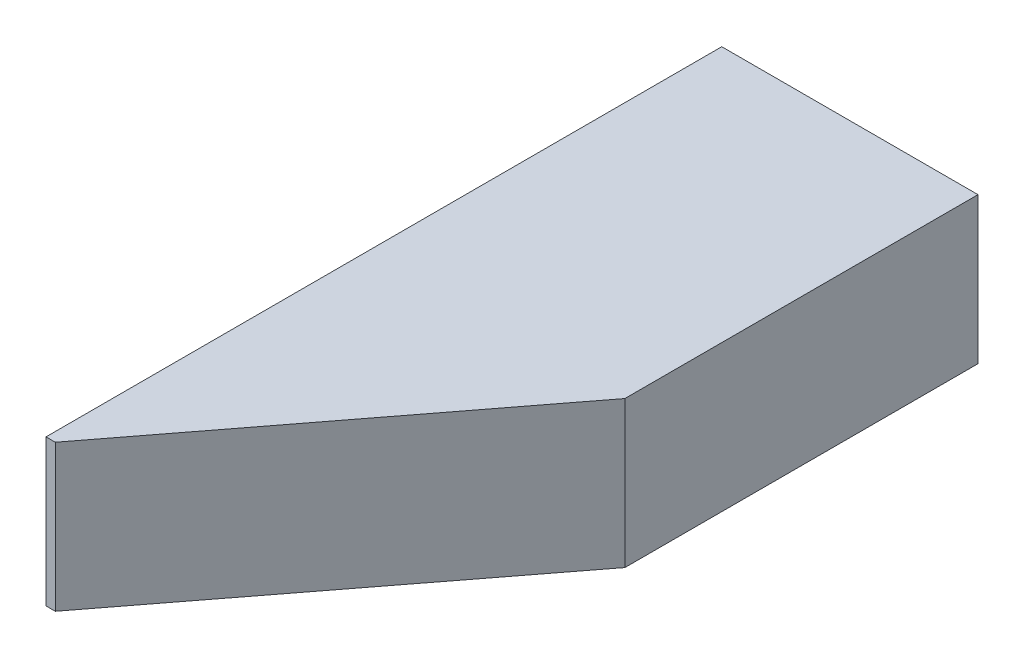
SolidWorks part; units mm, degrees
material "Pine"
ref_plane "X-Y Datum" through (0, 0, 0) normal (0, 0, 1) x (1, 0, 0)
ref_plane "X-Z Datum" through (0, 0, 0) normal (0, 1, 0) x (1, 0, 0)
ref_plane "Y-Z Datum" through (0, 0, 0) normal (1, 0, 0) x (0, 0, -1)
sketch "Sketch2" plane through (0, 0, 0) normal (0, 0, 1) x (1, 0, 0)
  line L1 (0, 0) -> (101.6, 0)
  line L2 (0, 0) -> (0, 50.8)
  line L3 (0, 50.8) -> (101.6, 50.8)
  line L4 (101.6, 0) -> (101.6, 50.8)
  dimension "D1" = 101.6
  dimension "D2" = 50.8
extrude "Boss-Extrude1" add sketch "Sketch2" along normal blind 122.5128
sketch "Sketch3" plane through (0, 50.8, 0) normal (0, 1, 0) x (1, 0, 0)
  line L0 (101.6, -122.5128) -> (15.9196, -234.4566)
  line L1 (0, -234.4566) -> (0, -122.5128)
  line L2 (0, -122.5128) -> (101.6, -122.5128)
  line L3 (15.9196, -234.4566) -> (0, -234.4566)
  dimension "D1" = 52.57
  dimension "D2" = 15.9196
extrude "Boss-Extrude2" add sketch "Sketch3" against normal up to surface (50.8 mm away) up to face at (50.8, 0, 61.2564)
sketch "Sketch4" plane through (0, 50.8, 0) normal (0, 1, 0) x (1, 0, 0)
  line L2 (12.7, -234.4566) -> (12.7, 0)
  line L3 (101.6, 0) -> (0, 0) construction
  line L4 (12.7, 0) -> (0, 0)
  line L5 (0, 0) -> (0, -234.4566)
  line L8 (101.6, -122.5128) -> (101.6, 0) construction
  line L9 (0, -234.4566) -> (15.9196, -234.4566) construction
  line L10 (12.7, -234.4566) -> (0, -234.4566)
  dimension "D1" = 88.9
extrude "Cut-Extrude1" cut sketch "Sketch4" against normal through all both
